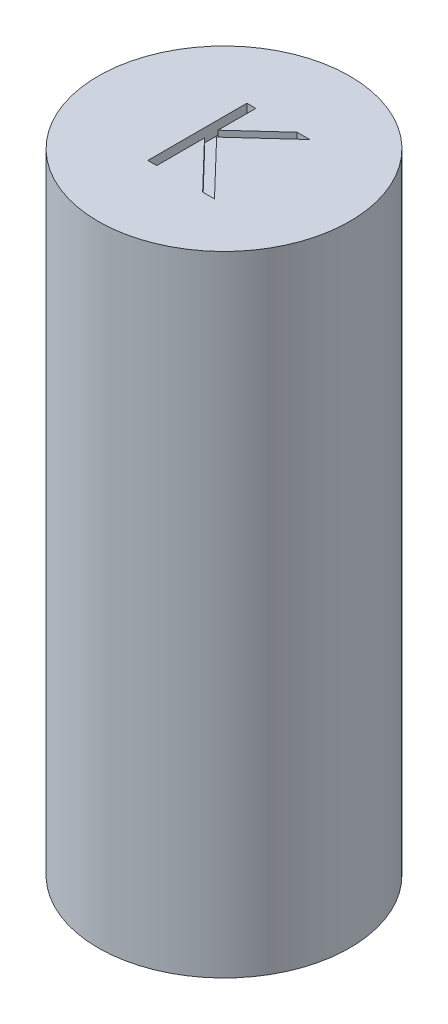
SolidWorks part; units mm, degrees
ref_plane "Front Plane" through (0, 0, 0) normal (0, 0, 1) x (1, 0, 0)
ref_plane "Top Plane" through (0, 0, 0) normal (0, 1, 0) x (1, 0, 0)
ref_plane "Right Plane" through (0, 0, 0) normal (1, 0, 0) x (0, 0, -1)
sketch "Sketch1" plane through (0, 0, 0) normal (0, 1, 0) x (1, 0, 0)
  circle A0 centre (0, 0) radius 19.05
  dimension "D1" = 38.1
extrude "Boss-Extrude1" add sketch "Sketch1" along normal blind 95.25
sketch "Sketch2" plane through (0, 95.25, 0) normal (0, 1, 0) x (1, 0, 0)
  line L0 (0, 19.05) -> (0, -19.05) construction
  line L1 (-17.5939, -7.3046) -> (17.5939, -7.3046) construction
  circle A0 centre (0, 0) radius 19.05 construction
  text T0 "K" font "Century Gothic" height 15
  point P8 (-19.05, 0)
extrude "Cut-Extrude1" cut sketch "Sketch2" against normal blind 2
